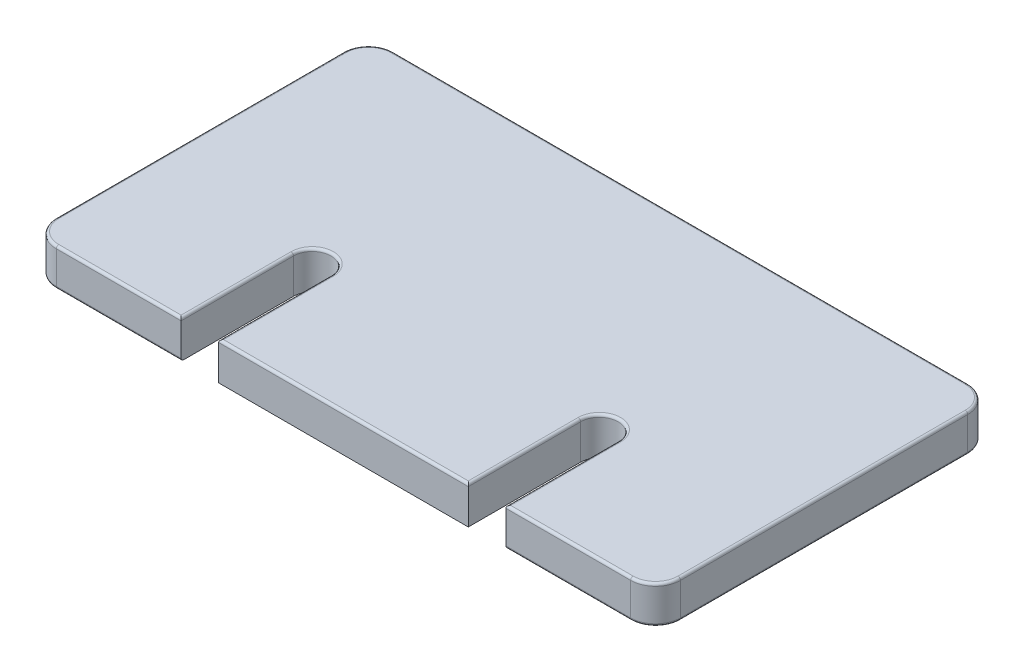
SolidWorks part; units mm, degrees
ref_plane "Front Plane" through (0, 0, 0) normal (0, 0, 1) x (1, 0, 0)
ref_plane "Top Plane" through (0, 0, 0) normal (0, 1, 0) x (1, 0, 0)
ref_plane "Right Plane" through (0, 0, 0) normal (1, 0, 0) x (0, 0, -1)
sketch "Sketch1" plane through (0, 0, 0) normal (0, 1, 0) x (1, 0, 0)
  line L0 (0, 0) -> (0, 27) construction
  line L1 (10, 0) -> (-10, 0)
  line L2 (-10, 9) -> (-10, 0)
  line L3 (-13, 9) -> (-13, 0)
  line L4 (-25, 2) -> (-25, 25)
  line L5 (-23, 27) -> (23, 27)
  line L6 (-13, 0) -> (-23, 0)
  line L7 (13, 0) -> (23, 0)
  line L8 (25, 2) -> (25, 25)
  line L9 (13, 9) -> (13, 0)
  line L10 (10, 9) -> (10, 0)
  arc A0 (-10, 9) -> (-13, 9) centre (-11.5, 9) ccw
  arc A1 (10, 9) -> (13, 9) centre (11.5, 9) cw
  arc A2 (23, 0) -> (25, 2) centre (23, 2) ccw
  arc A3 (25, 25) -> (23, 27) centre (23, 25) ccw
  arc A4 (-23, 0) -> (-25, 2) centre (-23, 2) cw
  arc A5 (-25, 25) -> (-23, 27) centre (-23, 25) cw
  point P19 (25, 0)
  point P22 (25, 27)
  point P25 (-25, 0)
  point P28 (-25, 27)
  dimension "D2" = 3
  dimension "D6" = 2
  dimension "D1" = 25
  dimension "D3" = 27
  dimension "D4" = 9
  dimension "D5" = 10
extrude "Boss-Extrude1" add sketch "Sketch1" along normal blind 3
ref_plane "Plane1" through (0, 0, -9) normal (0, 0, 1) x (0, -1, 0)
fillet "Fillet1" radius 0.2 25 edges at (18, 0, 0) (24.4142, 0, -0.5858) (25, 0, -13.5) (24.4142, 0, -26.4142) (0, 0, -27) (-24.4142, 0, -26.4142) (-25, 0, -13.5) (-24.4142, 0, -0.5858) (-13, 3, -4.5) (-18, 3, 0) (-24.4142, 3, -0.5858) (-25, 3, -13.5) (-24.4142, 3, -26.4142) (0, 3, -27) (24.4142, 3, -26.4142) (25, 3, -13.5) (24.4142, 3, -0.5858) (18, 3, 0) (13, 3, -4.5) (11.5, 3, -10.5) (10, 3, -4.5) (0, 3, 0) (-10, 3, -4.5) (-11.5, 3, -10.5) (-18, 0, 0)
